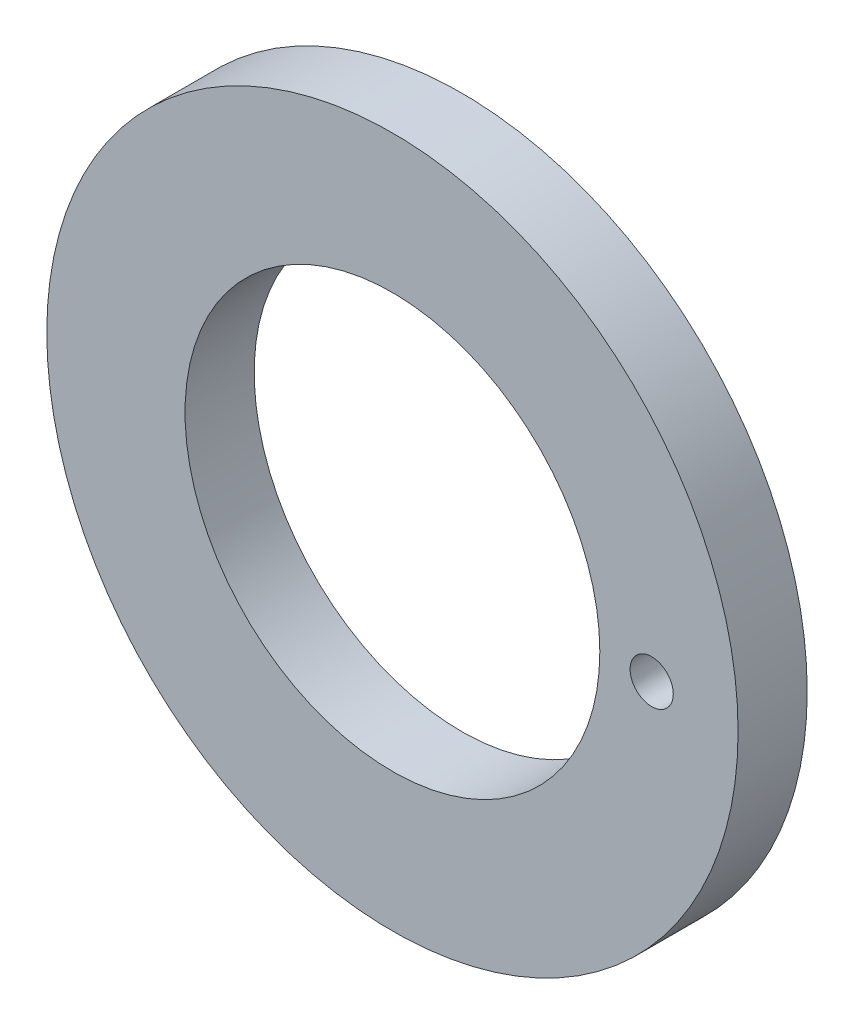
SolidWorks part; units mm, degrees
material "Beech"
ref_plane "Front Plane" through (0, 0, 0) normal (0, 0, 1) x (1, 0, 0)
ref_plane "Top Plane" through (0, 0, 0) normal (0, 1, 0) x (1, 0, 0)
ref_plane "Right Plane" through (0, 0, 0) normal (1, 0, 0) x (0, 0, -1)
sketch "Sketch1" plane through (0, 0, 0) normal (0, 0, 1) x (1, 0, 0)
  circle A0 centre (0, 0) radius 15.24
  circle A1 centre (0, 0) radius 25.4
  dimension "D1" = 30.48
  dimension "D2" = 50.8
extrude "Boss-Extrude1" add sketch "Sketch1" along normal blind 5.08
sketch "Sketch2" plane through (0, 0, 5.08) normal (0, 0, 1) x (1, 0, 0)
  circle A0 centre (19.05, 0) radius 1.5875
  circle A3 centre (0, 0) radius 25.4 construction
  point P2 (0, 0)
  point P4 (15.24, 0)
  point P8 (19.05, 0)
  dimension "D1" = 3.175
  dimension "D2" = 19.05
extrude "Cut-Extrude1" cut sketch "Sketch2" against normal through all
